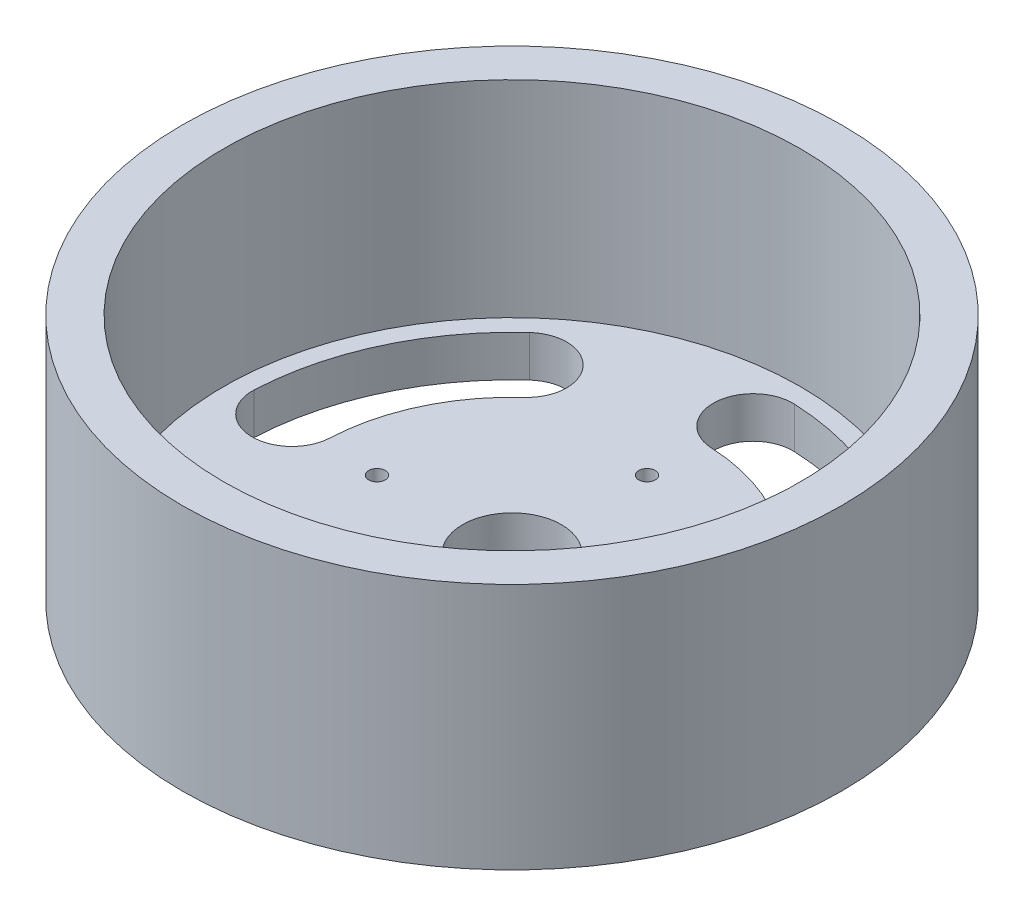
SolidWorks part; units mm, degrees
ref_plane "Front Plane" through (0, 0, 0) normal (0, 0, 1) x (1, 0, 0)
ref_plane "Top Plane" through (0, 0, 0) normal (0, 1, 0) x (1, 0, 0)
ref_plane "Right Plane" through (0, 0, 0) normal (1, 0, 0) x (0, 0, -1)
sketch "Sketch1" plane through (0, 0, 0) normal (0, 1, 0) x (1, 0, 0)
  circle A0 centre (0, 0) radius 40
  dimension "D1" = 80
extrude "Boss-Extrude1" add sketch "Sketch1" along normal blind 30
sketch "Sketch2" plane through (0, 30, 0) normal (0, 1, 0) x (1, 0, 0)
  circle A0 centre (0, 0) radius 35
  dimension "D1" = 70
extrude "Cut-Extrude1" cut sketch "Sketch2" against normal blind 25
sketch "Sketch4" plane through (0, 0, 0) normal (0, -1, 0) x (1, 0, 0)
  circle A1 centre (0, 0) radius 6
  circle A3 centre (0, 16.383) radius 1
  circle A4 centre (-16.383, 0) radius 1
  circle A5 centre (16.383, 0) radius 1
  circle A6 centre (0, -16.383) radius 1
  arc A7 (-20.6808, 18.8761) -> (-1.2761, 27.9709) centre (0, 0) cw construction
  arc A8 (-1.4962, 32.7935) -> (-24.2464, 22.1305) centre (0, 0) ccw
  arc A9 (-1.0561, 23.1483) -> (-17.1151, 15.6216) centre (0, 0) ccw
  arc A10 (-1.0561, 23.1483) -> (-1.4962, 32.7935) centre (-1.2761, 27.9709) ccw
  arc A11 (-24.2464, 22.1305) -> (-17.1151, 15.6216) centre (-20.6808, 18.8761) ccw
  arc A12 (18.8761, 20.6808) -> (27.9709, 1.2761) centre (0, 0) cw construction
  arc A13 (32.7935, 1.4962) -> (22.1305, 24.2464) centre (0, 0) ccw
  arc A14 (23.1483, 1.0561) -> (15.6216, 17.1151) centre (0, 0) ccw
  arc A15 (23.1483, 1.0561) -> (32.7935, 1.4962) centre (27.9709, 1.2761) ccw
  arc A16 (22.1305, 24.2464) -> (15.6216, 17.1151) centre (18.8761, 20.6808) ccw
  arc A17 (20.6808, -18.8761) -> (1.2761, -27.9709) centre (0, 0) cw construction
  arc A18 (1.4962, -32.7935) -> (24.2464, -22.1305) centre (0, 0) ccw
  arc A19 (1.0561, -23.1483) -> (17.1151, -15.6216) centre (0, 0) ccw
  arc A20 (1.0561, -23.1483) -> (1.4962, -32.7935) centre (1.2761, -27.9709) ccw
  arc A21 (24.2464, -22.1305) -> (17.1151, -15.6216) centre (20.6808, -18.8761) ccw
  arc A22 (-18.8761, -20.6808) -> (-27.9709, -1.2761) centre (0, 0) cw construction
  arc A23 (-32.7935, -1.4962) -> (-22.1305, -24.2464) centre (0, 0) ccw
  arc A24 (-23.1483, -1.0561) -> (-15.6216, -17.1151) centre (0, 0) ccw
  arc A25 (-23.1483, -1.0561) -> (-32.7935, -1.4962) centre (-27.9709, -1.2761) ccw
  arc A26 (-22.1305, -24.2464) -> (-15.6216, -17.1151) centre (-18.8761, -20.6808) ccw
  point P15 (-11.883, 25.3534)
  point P25 (25.3534, 11.883)
  point P32 (11.883, -25.3534)
  point P39 (-25.3534, -11.883)
  point P44 (0, 0)
  dimension "D2" = 4
extrude "Cut-Extrude2" cut sketch "Sketch4" against normal up to next
